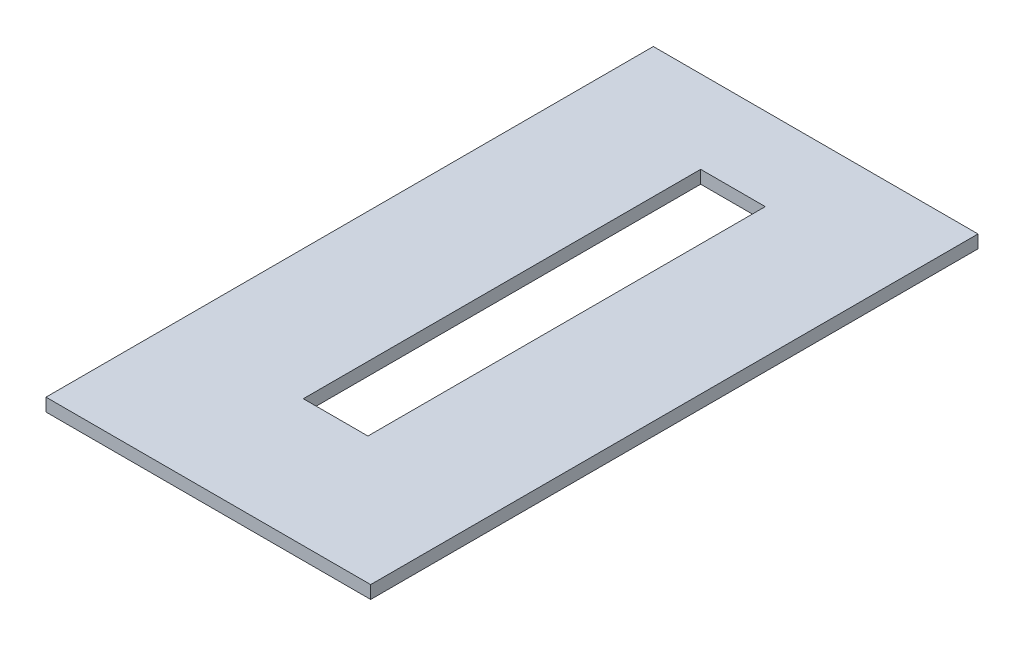
SolidWorks part; units mm, degrees
material "AISI 1020"
ref_plane "Спереди" through (0, 0, 0) normal (0, 0, 1) x (1, 0, 0)
ref_plane "Сверху" through (0, 0, 0) normal (0, 1, 0) x (1, 0, 0)
ref_plane "Справа" through (0, 0, 0) normal (1, 0, 0) x (0, 0, -1)
sketch "Эскиз1" plane through (0, 0, 0) normal (0, 1, 0) x (1, 0, 0)
  line L1 (-2512.5, 4700) -> (2512.5, 4700)
  line L2 (-2512.5, 4700) -> (-2512.5, -4700)
  line L3 (-2512.5, -4700) -> (2512.5, -4700)
  line L4 (2512.5, 4700) -> (2512.5, -4700)
extrude "Бобышка-Вытянуть1" add sketch "Эскиз1" against normal blind 200
sketch "Эскиз2" plane through (0, 0, 0) normal (0, 1, 0) x (1, 0, 0)
  line L1 (500, 3420) -> (-500, 3420)
  line L2 (500, 3420) -> (500, -2730)
  line L3 (500, -2730) -> (-500, -2730)
  line L4 (-500, 3420) -> (-500, -2730)
extrude "Вырез-Вытянуть1" cut sketch "Эскиз2" against normal through all
